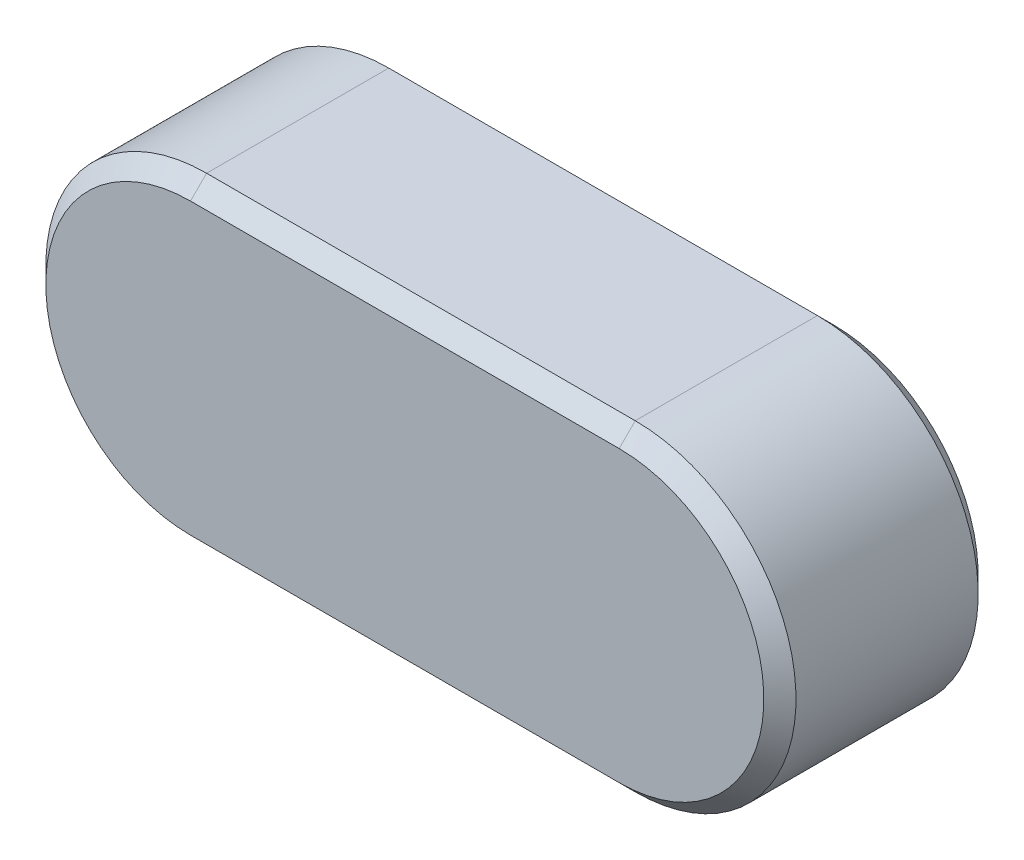
SolidWorks part; units mm, degrees
ref_plane "Front" through (0, 0, 0) normal (0, 0, 1) x (1, 0, 0)
ref_plane "Top" through (0, 0, 0) normal (0, 1, 0) x (1, 0, 0)
ref_plane "Right" through (0, 0, 0) normal (1, 0, 0) x (0, 0, -1)
sketch "Sketch1" plane through (0, 0, 0) normal (0, 0, 1) x (1, 0, 0)
  line L0 (-16, 6) -> (0, 6)
  line L1 (0, -6) -> (-16, -6)
  arc A0 (0, 6) -> (0, -6) centre (0, 0) cw
  arc A1 (-16, -6) -> (-16, 6) centre (-16, 0) cw
  dimension "L" = 28
  dimension "b" = 12
extrude "BaseKey" add sketch "Sketch1" along normal mid plane 8
sketch "Sketch2" plane through (0, 0, 0) normal (0, 0, 1) x (1, 0, 0)
  line L1 (-22, 6) -> (6, 6)
  line L2 (-22, 6) -> (-22, -6)
  line L3 (-22, -6) -> (6, -6)
  line L4 (6, 6) -> (6, -6)
  line L6 (0, -6) -> (-16, -6) construction
  line L7 (-16, 6) -> (0, 6) construction
  arc A2 (0, -6) -> (0, 6) centre (0, 0) ccw construction
  arc A3 (-16, 6) -> (-16, -6) centre (-16, 0) ccw construction
extrude "Extrude1" [suppressed] add sketch "Sketch2" along normal mid plane 8
sketch "Sketch3" plane through (0, 0, 0) normal (0, 0, 1) x (1, 0, 0)
  line L0 (6, 6) -> (-16, 6)
  line L1 (-16, -6) -> (6, -6)
  line L2 (6, -6) -> (6, 6)
  line L5 (-16, 6) -> (0, 6) construction
  arc A0 (-16, 6) -> (-16, -6) centre (-16, 0) ccw
  arc A1 (0, -6) -> (0, 6) centre (0, 0) ccw construction
  arc A4 (-16, 6) -> (-16, -6) centre (-16, 0) ccw construction
extrude "Extrude2" [suppressed] add sketch "Sketch3" along normal mid plane 8
chamfer "Chamfer1" distance 0.6 angle 45 8 edges at (6, 0, -4) (-8, -6, -4) (-22, 0, -4) (-8, 6, -4) (-22, 0, 4) (-8, -6, 4) (6, 0, 4) (-8, 6, 4)
equation "\"D1@Extrude1\"=\"h@BaseKey\""
equation "\"D1@Extrude2\"=\"h@BaseKey\""
